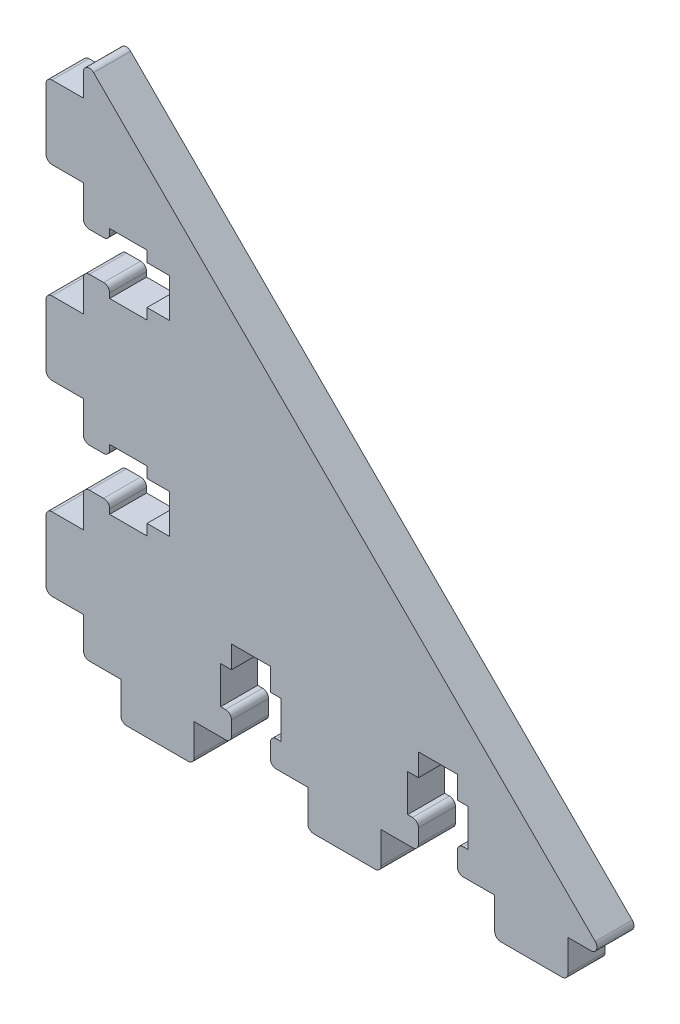
SolidWorks part; units mm, degrees
material "6061 Alloy"
ref_plane "Front Plane" through (0, 0, 0) normal (0, 0, 1) x (1, 0, 0)
ref_plane "Top Plane" through (0, 0, 0) normal (0, 1, 0) x (1, 0, 0)
ref_plane "Right Plane" through (0, 0, 0) normal (1, 0, 0) x (0, 0, -1)
sketch "Sketch2" plane through (0, 0, 0) normal (0, 0, 1) x (1, 0, 0)
  line L0 (11.5, 22.4) -> (-5, 22.4) construction
  line L1 (11.5, 25) -> (8.5, 25)
  line L2 (8.5, 25) -> (8.5, 26.45)
  line L3 (8.5, 26.45) -> (3.5, 26.45)
  line L4 (3.5, 26.45) -> (3.5, 25)
  line L5 (3.5, 25) -> (0, 25)
  line L6 (0, 25) -> (0, 30)
  line L7 (0, 30) -> (-5, 30)
  line L8 (-5, 30) -> (-5, 39.8)
  line L9 (-5, 39.8) -> (0, 39.8)
  line L10 (11.5, 25) -> (11.5, 19.8)
  line L11 (11.5, 19.8) -> (8.5, 19.8)
  line L12 (8.5, 19.8) -> (8.5, 18.35)
  line L13 (8.5, 18.35) -> (3.5, 18.35)
  line L14 (3.5, 18.35) -> (3.5, 19.8)
  line L15 (3.5, 19.8) -> (0, 19.8)
  line L16 (0, 19.8) -> (0, 14.8)
  line L17 (0, 14.8) -> (-5, 14.8)
  line L18 (-5, 14.8) -> (-5, 5)
  line L19 (-5, 5) -> (0, 5)
  line L20 (0, 5) -> (0, 0)
  line L21 (0, 0) -> (39.1305, 39.1305) construction
  line L22 (0, 39.8) -> (0, 44.8)
  line L23 (0, 69.8) -> (69.8, 0)
  line L24 (8.5, 43.35) -> (3.5, 43.35)
  line L25 (3.5, 43.35) -> (3.5, 44.8)
  line L26 (11.5, 44.8) -> (8.5, 44.8)
  line L27 (8.5, 44.8) -> (8.5, 43.35)
  line L28 (3.5, 44.8) -> (0, 44.8)
  line L29 (3.5, 50) -> (0, 50)
  line L30 (3.5, 51.45) -> (3.5, 50)
  line L31 (8.5, 51.45) -> (3.5, 51.45)
  line L32 (8.5, 50) -> (8.5, 51.45)
  line L33 (11.5, 50) -> (8.5, 50)
  line L34 (11.5, 50) -> (11.5, 44.8)
  line L35 (0, 50) -> (0, 55)
  line L36 (-5, 55) -> (-5, 64.8)
  line L37 (0, 55) -> (-5, 55)
  line L38 (-5, 64.8) -> (0, 64.8)
  line L39 (0, 64.8) -> (0, 69.8)
  line L40 (22.4, 11.5) -> (22.4, -5) construction
  line L41 (19.8, 3.5) -> (19.685, 3.4577)
  line L42 (64.8, 0) -> (69.8, 0)
  line L43 (64.8, -5) -> (64.8, 0)
  line L44 (3.5, 19.8) -> (3.4577, 19.685)
  line L45 (0, 44.8) -> (0, 39.8) [skipped]
  line L46 (55, 0) -> (55, -5)
  line L47 (55, -5) -> (64.8, -5)
  line L48 (50, 0) -> (55, 0)
  line L49 (50, 11.5) -> (44.8, 11.5)
  line L50 (50, 11.5) -> (50, 8.5)
  line L51 (50, 8.5) -> (51.45, 8.5)
  line L52 (51.45, 8.5) -> (51.45, 3.5)
  line L53 (51.45, 3.5) -> (50, 3.5)
  line L54 (50, 3.5) -> (50, 0)
  line L55 (44.8, 3.5) -> (44.8, 0)
  line L56 (44.8, 8.5) -> (43.35, 8.5)
  line L57 (44.8, 11.5) -> (44.8, 8.5)
  line L58 (43.35, 3.5) -> (44.8, 3.5)
  line L59 (43.35, 8.5) -> (43.35, 3.5)
  line L60 (39.8, 0) -> (44.8, 0)
  line L61 (5, 0) -> (0, 0)
  line L62 (5, -5) -> (5, 0)
  line L63 (14.8, -5) -> (5, -5)
  line L64 (14.8, 0) -> (14.8, -5)
  line L65 (19.8, 0) -> (14.8, 0)
  line L66 (19.8, 3.5) -> (19.8, 0)
  line L67 (18.35, 3.5) -> (19.8, 3.5)
  line L68 (18.35, 8.5) -> (18.35, 3.5)
  line L69 (19.8, 8.5) -> (18.35, 8.5)
  line L70 (19.8, 11.5) -> (19.8, 8.5)
  line L71 (25, 11.5) -> (19.8, 11.5)
  line L72 (39.8, -5) -> (39.8, 0)
  line L73 (30, -5) -> (39.8, -5)
  line L74 (30, 0) -> (30, -5)
  line L75 (25, 0) -> (30, 0)
  line L76 (25, 3.5) -> (25, 0)
  line L77 (26.45, 3.5) -> (25, 3.5)
  line L78 (26.45, 8.5) -> (26.45, 3.5)
  line L79 (25, 8.5) -> (26.45, 8.5)
  line L80 (25, 11.5) -> (25, 8.5)
  point P27 (39.1305, 39.1305)
  point P68 (34.9, 34.9)
  dimension "D1" = 45
  dimension "D2" = 2.6
  dimension "D3" = 3.5
  dimension "D4" = 5
  dimension "D5" = 3
  dimension "D6" = 4.05
  dimension "D7" = 5
  dimension "D8" = 5
  dimension "D9" = 5
  dimension "D10" = 2
  dimension "D11" = 9.8
extrude "Boss-Extrude1" add sketch "Sketch2" along normal blind 4.95
fillet "Fillet1" radius 0.8 31 edges at (-5, 30, 2.475) (-5, 14.8, 2.475) (-5, 5, 2.475) (0, 69.8, 2.475) (-5, 64.8, 2.475) (-5, 55, 2.475) (0, 50, 2.475) (0, 44.8, 2.475) (-5, 39.8, 2.475) (0, 25, 2.475) (0, 19.8, 2.475) (69.8, 0, 2.475) (64.8, -5, 2.475) (55, -5, 2.475) (50, 0, 2.475) (44.8, 0, 2.475) (39.8, -5, 2.475) (30, -5, 2.475) (19.8, 0, 2.475) (25, 0, 2.475) (14.8, -5, 2.475) (5, -5, 2.475) (0, 0, 2.475) (50, 3.5, 2.475) (44.8, 3.5, 2.475) (25, 3.5, 2.475) (19.8, 3.5, 2.475) (3.5, 50, 2.475) (3.5, 44.8, 2.475) (3.5, 25, 2.475) (3.5, 19.8, 2.475)
ref_plane "Plane3" through (0, 9.9, 0) normal (0, 1, 0) x (1, 0, 0)
ref_plane "Plane4" through (0, 34.9, 0) normal (0, -1, 0) x (-1, 0, 0)
ref_plane "Plane5" through (34.9, 0, 0) normal (1, 0, 0) x (0, 0, -1)
